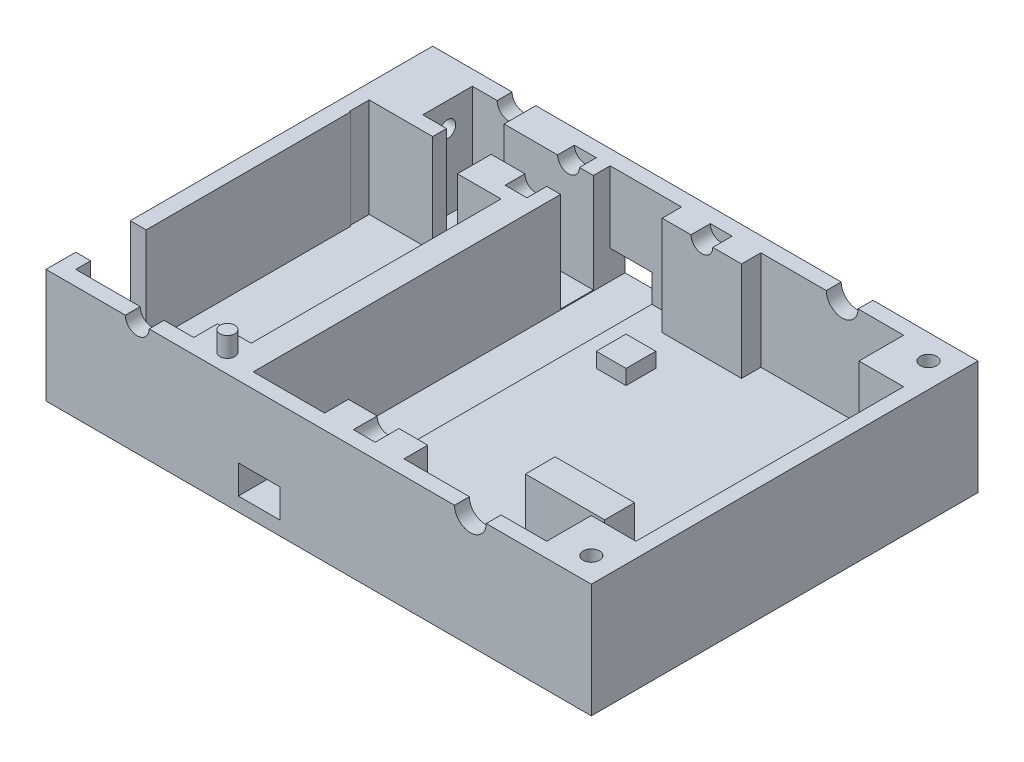
SolidWorks part; units mm, degrees
ref_plane "前视基准面" through (0, 0, 0) normal (0, 0, 1) x (1, 0, 0)
ref_plane "上视基准面" through (0, 0, 0) normal (0, 1, 0) x (1, 0, 0)
ref_plane "右视基准面" through (0, 0, 0) normal (1, 0, 0) x (0, 0, -1)
other "Configuration Table"
sketch "草图1" plane through (0, 0, 0) normal (0, 1, 0) x (1, 0, 0)
  line L1 (-27.5, 19.5) -> (27.5, 19.5)
  line L2 (-27.5, 19.5) -> (-27.5, -19.5)
  line L3 (-27.5, -19.5) -> (27.5, -19.5)
  line L4 (27.5, 19.5) -> (27.5, -19.5)
  line L5 (-27.5, 19.5) -> (27.5, -19.5) construction
  line L6 (-27.5, -19.5) -> (27.5, 19.5) construction
  point P0 (0, 0)
  dimension "D1" = 55
  dimension "D2" = 39
extrude "凸台-拉伸1" add sketch "草图1" along normal blind 11.5
shell "抽壳1" thickness 1.5
sketch "草图2" plane through (0, 0, -19.5) normal (0, 0, -1) x (-1, 0, 0)
  line L0 (7.9, 1.6) -> (4.1, 1.6) construction
  line L1 (3.9, 4.3) -> (8.1, 4.3)
  line L2 (3.9, 4.3) -> (3.9, 1.4)
  line L3 (3.9, 1.4) -> (8.1, 1.4)
  line L4 (8.1, 4.3) -> (8.1, 1.4)
  line L5 (7.9, 1.6) -> (7.9, 4.1) construction
  line L6 (7.9, 4.1) -> (4.1, 4.1) construction
  line L7 (4.1, 1.6) -> (4.1, 4.1) construction
  circle A0 centre (-15.3, 11.5) radius 1.6
  circle A1 centre (18.3, 11.5) radius 1.2
  circle A2 centre (-15.3, 11.5) radius 1.5 construction
  circle A3 centre (18.3, 11.5) radius 1 construction
  dimension "D1" = 0.1
  dimension "D2" = 0.2
  dimension "D3" = 0.2
  dimension "D4" = 0.2
  dimension "D5" = 0.2
  dimension "D6" = 0.2
extrude "切除-拉伸1" cut sketch "草图2" against normal through all
sketch "草图3" plane through (0, 1.5, 0) normal (0, 1, 0) x (1, 0, 0)
  line L0 (-25.8, -15.5) -> (-10.8, -15.5) construction
  line L5 (-10.7, 9.6) -> (-10.7, -15.6)
  line L6 (-15.1, 13) -> (-8.1, 13)
  line L7 (-15.1, 13) -> (-15.1, 9.6)
  line L8 (-15.1, 9.6) -> (-10.7, 9.6)
  line L10 (-17.1, -18) -> (13.7, -18) construction
  line L11 (-10.7, -18) -> (-8.1, -18)
  line L13 (-14.3, -17.8) -> (-14.3, -15.5) construction
  line L14 (-28.8, -11) -> (-25.8, -11) construction
  line L15 (-26, 9.6) -> (-25.9, 9.6)
  line L16 (-15.3, 9.5) -> (-15.3, 11.5) construction
  line L17 (-10.8, 9.5) -> (-10.8, -15.5) construction
  line L18 (-8.1, 18) -> (-8.1, -18) construction
  line L19 (13.7, 18) -> (-17.1, 18) construction
  line L20 (-17.1, 18) -> (-8.1, 18)
  line L21 (-17.1, 18) -> (-17.1, 16.3)
  line L22 (-17.1, 16.3) -> (-8.1, 16.3)
  line L23 (-8.1, 18) -> (-8.1, 16.3)
  line L24 (-17.1, 18) -> (-17.1, 19.5) construction
  line L25 (-8.1, 13) -> (-8.1, -18)
  line L26 (4.6159, 15.85) -> (4.2435, 15.85) construction
  line L27 (-0.9, 18) -> (7.1, 18)
  line L28 (-0.9, 18) -> (-0.9, 16.05)
  line L29 (-0.9, 16.05) -> (7.1, 16.05)
  line L30 (7.1, 18) -> (7.1, 16.05)
  line L31 (4.1, -18.1452) -> (4.1, 18.1548) construction
  line L32 (-17.1, -18) -> (13.7, -18) construction
  line L33 (-0.9, -15.6) -> (7.1, -15.6)
  line L34 (-0.9, -15.6) -> (-0.9, -18)
  line L35 (-0.9, -18) -> (7.1, -18)
  line L36 (7.1, -15.6) -> (7.1, -18)
  line L37 (-26, 9.6) -> (-26, -11)
  line L38 (26, 18) -> (16.9, 18) construction
  line L39 (21.5, 18) -> (26, 18)
  line L40 (21.5, 18) -> (21.5, 13.5)
  line L41 (21.5, 13.5) -> (26, 13.5)
  line L42 (26, 18) -> (26, 13.5)
  line L43 (26, -18) -> (26, 18) construction
  line L44 (-26, 18) -> (-26, -18) construction
  line L45 (21.5, -13.5) -> (26, -13.5)
  line L46 (21.5, -13.5) -> (21.5, -18)
  line L47 (21.5, -18) -> (26, -18)
  line L48 (26, -13.5) -> (26, -18)
  line L49 (-26, 18) -> (-22, 18)
  line L50 (-26, 18) -> (-26, 13)
  line L52 (-22, 18) -> (-22, 13)
  line L53 (-26, 11.6) -> (-19.6, 11.6)
  line L54 (-26, 11.6) -> (-26, 13)
  line L55 (-22, 13) -> (-19.6, 13)
  line L56 (-19.6, 11.6) -> (-19.6, 13)
  line L57 (-15.3, 11.5) -> (-21.3, 11.5) construction
  line L58 (-19.3, 19) -> (-19.3, 11.5) construction
  line L59 (-10.8, 9.5) -> (-25.8, 9.5) construction
  line L60 (-19.5, 18) -> (-26, 18) construction
  line L61 (-26, -11) -> (-25.9, -11)
  line L62 (-14.1, -15.6) -> (-10.7, -15.6)
  line L63 (-14.1, -15.6) -> (-14.1, -18)
  line L64 (-14.1, -18) -> (-10.7, -18)
  line L65 (-25.9, 9.6) -> (-25.9, -11)
  dimension "D2" = 4
  dimension "D3" = 0.1
  dimension "D4" = 0.2
  dimension "D5" = 1.7
  dimension "D6" = 0.1
  dimension "D7" = 8
  dimension "D8" = 0.2
  dimension "D9" = 3
  dimension "D10" = 8
  dimension "D11" = 3
  dimension "D12" = 2.4
  dimension "D13" = 4.5
  dimension "D14" = 4.5
  dimension "D15" = 4.5
  dimension "D16" = 4.5
  dimension "D17" = 0.3
  dimension "D18" = 0.1
  dimension "D19" = 5
  dimension "D20" = 0.1
  dimension "D21" = 0.2
  dimension "D22" = 0.1
extrude "凸台-拉伸2" add sketch "草图3" along normal up to surface (10 mm away) up to face at (-23.125, 11.5, 0)
sketch "草图4" plane through (0, 0, 19.5) normal (0, 0, 1) x (1, 0, 0)
  circle A0 centre (3.1, 11.5) radius 1.1
  circle A1 centre (3.1, 11.5) radius 1 construction
  dimension "D1" = 0.1
extrude "切除-拉伸2" cut sketch "草图4" against normal offset from surface (36 mm away) 1.5 from offset 1.5 up to face at (-6, 2.85, -19.5) offset against normal yes
sketch "草图5" plane through (0, 0, -19.5) normal (0, 0, -1) x (-1, 0, 0)
  circle A0 centre (10.6, 11.5) radius 1.1
  circle A1 centre (10.6, 11.5) radius 1 construction
  dimension "D1" = 0.1
extrude "切除-拉伸3" cut sketch "草图5" against normal blind 7 from offset 1.5 offset against normal yes
sketch "草图6" plane through (0, 1.5, 0) normal (0, 1, 0) x (1, 0, 0)
  line L0 (-0.9, 18) -> (-8.1, 18) construction
  line L1 (-1.1, 12.6) -> (1.9, 12.6)
  line L2 (-1.1, 12.6) -> (-1.1, 9.6)
  line L3 (-1.1, 9.6) -> (1.9, 9.6)
  line L4 (1.9, 12.6) -> (1.9, 9.6)
  line L6 (-8.1, -18) -> (-8.1, 13) construction
  line L8 (-32, 4) -> (-27.5, 4)
  line L9 (-32, 4) -> (-32, -4)
  line L10 (-32, -4) -> (-27.5, -4)
  line L11 (-27.5, 4) -> (-27.5, -4)
  line L14 (-27.5, 0) -> (-45.462, 0) construction
  line L15 (-27.5, 19.5) -> (-27.5, -19.5) construction
  dimension "D1" = 8.4
  dimension "D2" = 3
  dimension "D3" = 3
  dimension "D4" = 7
  dimension "D5" = 4.5
  dimension "D6" = 8
extrude "变速卡位凸台-拉伸3" add sketch "草图6" along normal blind 1.5 and the other way blind 1.5
sketch "草图7" plane through (0, 0, 0) normal (0, -1, 0) x (1, 0, 0)
  line L0 (-32, -4) -> (-32, 4) construction
  line L1 (27.5, 0) -> (56.3628, 0) construction
  line L2 (27.5, 19.5) -> (27.5, -19.5) construction
  line L3 (21.5, 13.5) -> (21.5, 18) construction
  line L4 (26, 13.5) -> (21.5, 13.5) construction
  circle A0 centre (-29.8, 0) radius 1
  circle A1 centre (25, 17) radius 0.825
  circle A2 centre (25, -17) radius 0.825
  dimension "D1" = 2
  dimension "D2" = 2.2
  dimension "D3" = 1.65
  dimension "D4" = 3.5
  dimension "D5" = 3.5
extrude "盖子固定切除-拉伸4" cut sketch "草图7" against normal through all
sketch "草图8" plane through (0, 1.5, 0) normal (0, 1, 0) x (1, 0, 0)
  line L0 (27.5, 0) -> (45.6897, 0) construction
  line L1 (27.5, -19.5) -> (27.5, 19.5) construction
  line L2 (26, -13.5) -> (26, 13.5) construction
  line L3 (26, -13.5) -> (21.5, -13.5) construction
  circle A0 centre (23, 7.6) radius 1
  circle A1 centre (23, -10.5) radius 1
  dimension "D1" = 2
  dimension "D2" = 3
  dimension "D3" = 3
  dimension "D4" = 2
  dimension "D5" = 3
  dimension "D6" = 3
extrude "底部螺丝孔切除-拉伸5" cut sketch "草图8" against normal through all
sketch "草图9" plane through (-27.5, 0, 0) normal (-1, 0, 0) x (0, 0, 1)
  line L0 (-19.5, 11.5) -> (19.5, 11.5) construction
  line L1 (-18, 11.5) -> (-18, 1.5) construction
  circle A0 centre (-15.502, 9) radius 0.825
  dimension "D1" = 1.65
  dimension "D2" = 2.5
  dimension "D3" = 2.498
extrude "前螺丝孔切除-拉伸6" cut sketch "草图9" against normal up to next
sketch "草图10" plane through (0, 1.5, 0) normal (0, 1, 0) x (1, 0, 0)
  line L0 (16.8, -25.8525) -> (16.8, 20.1475) construction
  line L1 (11.55, -7.2) -> (19.55, -7.2)
  line L2 (11.55, -7.2) -> (11.55, -10.2)
  line L3 (11.55, -10.2) -> (19.55, -10.2)
  line L4 (19.55, -7.2) -> (19.55, -10.2)
  line L5 (16.0993, -7.1) -> (16.9803, -7.1) construction
  dimension "D1" = 8
  dimension "D2" = 2.75
  dimension "D3" = 0.1
  dimension "D4" = 3
extrude "3mm轴卡位凸台-拉伸4" add sketch "草图10" along normal blind 7
sketch "草图11" plane through (-27.5, 0, 0) normal (-1, 0, 0) x (0, 0, 1)
  line L1 (16.5, 3.5) -> (11, 3.5)
  line L2 (16.5, 3.5) -> (16.5, 11.5)
  line L3 (16.5, 11.5) -> (11, 11.5)
  line L4 (11, 3.5) -> (11, 11.5)
  line L5 (-19.5, 11.5) -> (19.5, 11.5) construction
  line L6 (11, 7.5) -> (11, 3.5) construction
extrude "切除-拉伸4" cut sketch "草图11" against normal up to next
sketch "草图12" plane through (0, 11.5, 0) normal (0, 1, 0) x (1, 0, 0)
  line L0 (-8.1, -18) -> (-8.1, 13) construction
  line L1 (-10.7, -15.6) -> (-14.1, -15.6) construction
  circle A0 centre (-11.1, -17.6) radius 0.75
  dimension "D1" = 1.5
  dimension "D2" = 3
  dimension "D3" = 2
extrude "凸台-拉伸5" add sketch "草图12" along normal blind 2
